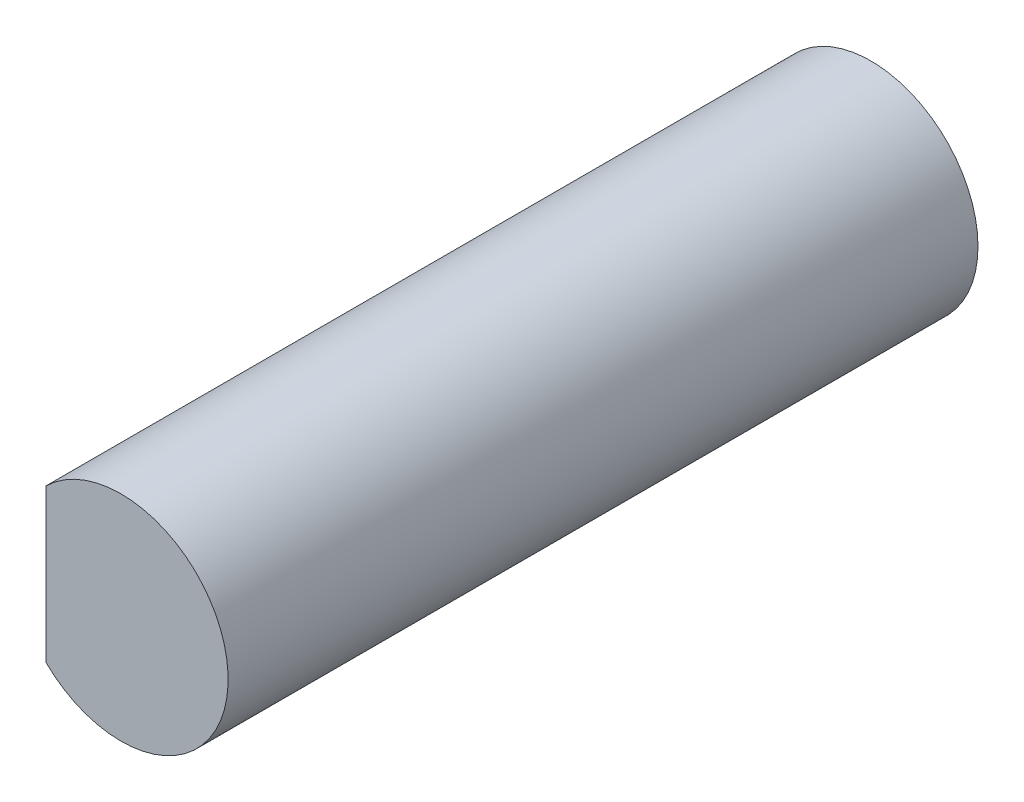
SolidWorks part; units mm, degrees
ref_plane "정면" through (0, 0, 0) normal (0, 0, 1) x (1, 0, 0)
ref_plane "윗면" through (0, 0, 0) normal (0, 1, 0) x (1, 0, 0)
ref_plane "우측면" through (0, 0, 0) normal (1, 0, 0) x (0, 0, -1)
sketch "스케치1" plane through (0, 0, 0) normal (0, 0, 1) x (1, 0, 0)
  circle A0 centre (0, 0) radius 5
  dimension "D1" = 10
extrude "보스-돌출1" add sketch "스케치1" along normal blind 25
sketch "스케치2" plane through (0, 0, 25) normal (0, 0, 1) x (1, 0, 0)
  line L0 (-3.5, 3.5707) -> (-3.5, -3.5707)
  arc A0 (-3.5, -3.5707) -> (-3.5, 3.5707) centre (0, 0) ccw
  circle A1 centre (0, 0) radius 5 construction
  dimension "D1" = 3.5
extrude "컷-돌출1" cut sketch "스케치2" against normal blind 15 flip side to cut
sketch "스케치3" plane through (0, 0, 0) normal (0, 0, -1) x (-1, 0, 0)
  circle A0 centre (0, 0) radius 5
extrude "보스-돌출2" add sketch "스케치3" along normal blind 10
